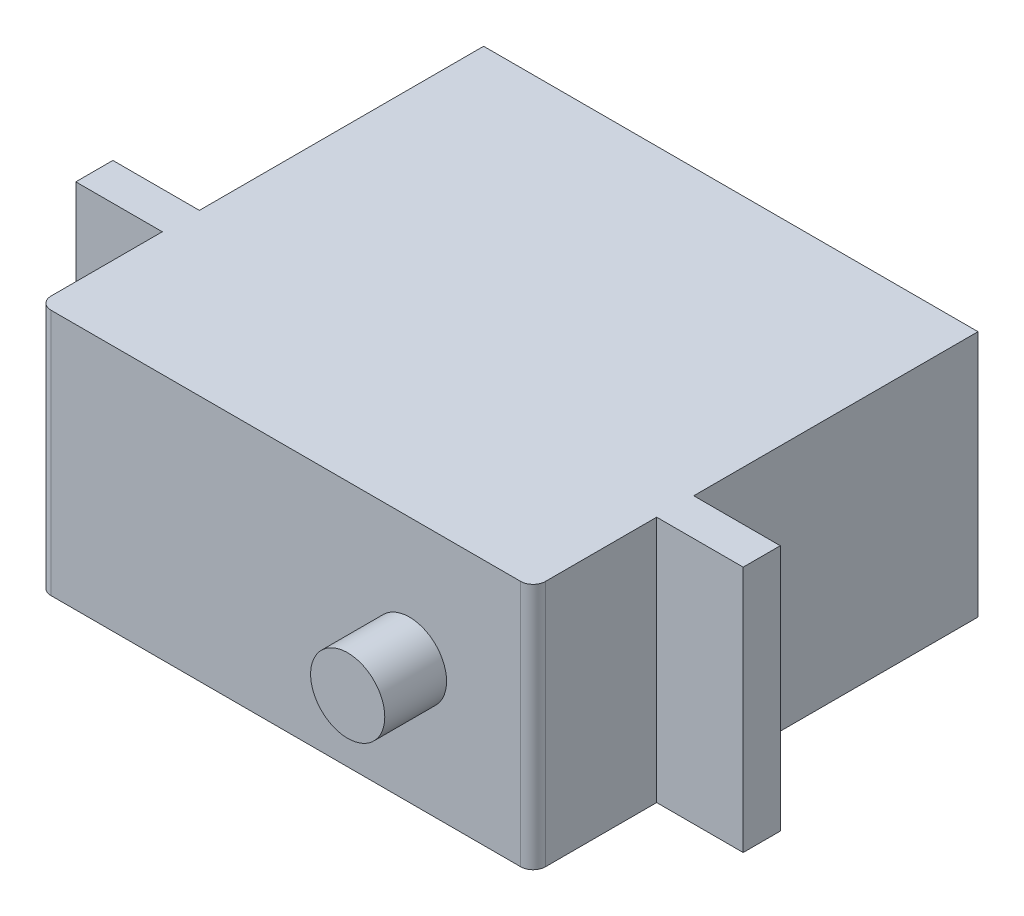
SolidWorks part; units mm, degrees
ref_plane "Plan de face" through (0, 0, 0) normal (0, 0, 1) x (1, 0, 0)
ref_plane "Plan de dessus" through (0, 0, 0) normal (0, 1, 0) x (1, 0, 0)
ref_plane "Plan de droite" through (0, 0, 0) normal (1, 0, 0) x (0, 0, -1)
sketch "Esquisse1" plane through (0, 0, 0) normal (0, 0, 1) x (1, 0, 0)
  line L1 (-24.886, 10.2907) -> (15.114, 10.2907)
  line L2 (-24.886, 10.2907) -> (-24.886, -9.7093)
  line L3 (-24.886, -9.7093) -> (15.114, -9.7093)
  line L4 (15.114, 10.2907) -> (15.114, -9.7093)
  dimension "D1" = 40
  dimension "D2" = 20
extrude "Boss.-Extru.1" add sketch "Esquisse1" along normal blind 36
sketch "Esquisse2" plane through (15.114, 0, 0) normal (1, 0, 0) x (0, 0, -1)
  line L0 (-36, 10.2907) -> (0, 10.2907) construction
  line L1 (-26, 10.2907) -> (-23, 10.2907)
  line L2 (-26, 10.2907) -> (-26, -9.7093)
  line L3 (-26, -9.7093) -> (-23, -9.7093)
  line L4 (-23, 10.2907) -> (-23, -9.7093)
  line L5 (-36, -9.7093) -> (0, -9.7093) construction
  line L6 (-36, -9.7093) -> (-36, 10.2907) construction
  point P8 (-27.3308, -12.358)
  dimension "D1" = 10
  dimension "D2" = 3
extrude "Boss.-Extru.2" add sketch "Esquisse2" along normal blind 7
sketch "Esquisse3" plane through (-24.886, 0, 0) normal (-1, 0, 0) x (0, 0, 1)
  line L0 (36, 10.2907) -> (0, 10.2907) construction
  line L1 (26, 10.2907) -> (23, 10.2907)
  line L2 (26, 10.2907) -> (26, -9.7093)
  line L3 (26, -9.7093) -> (23, -9.7093)
  line L4 (23, 10.2907) -> (23, -9.7093)
  line L5 (36, -9.7093) -> (0, -9.7093) construction
  line L6 (36, 10.2907) -> (36, -9.7093) construction
  dimension "D1" = 3
  dimension "D2" = 10
extrude "Boss.-Extru.3" add sketch "Esquisse3" along normal blind 7
sketch "Esquisse4" plane through (0, 0, 36) normal (0, 0, 1) x (1, 0, 0)
  line L0 (15.114, 10.2907) -> (15.114, -9.7093) construction
  line L1 (15.114, 10.2907) -> (-24.886, 10.2907) construction
  circle A0 centre (5.114, 0.2907) radius 3
  dimension "D1" = 10
  dimension "D2" = 10
  dimension "D3" = 6
extrude "Boss.-Extru.4" add sketch "Esquisse4" along normal blind 5
fillet "Congé1" radius 1 2 edges at (15.114, 0.2907, 36) (-24.886, 0.2907, 36)
